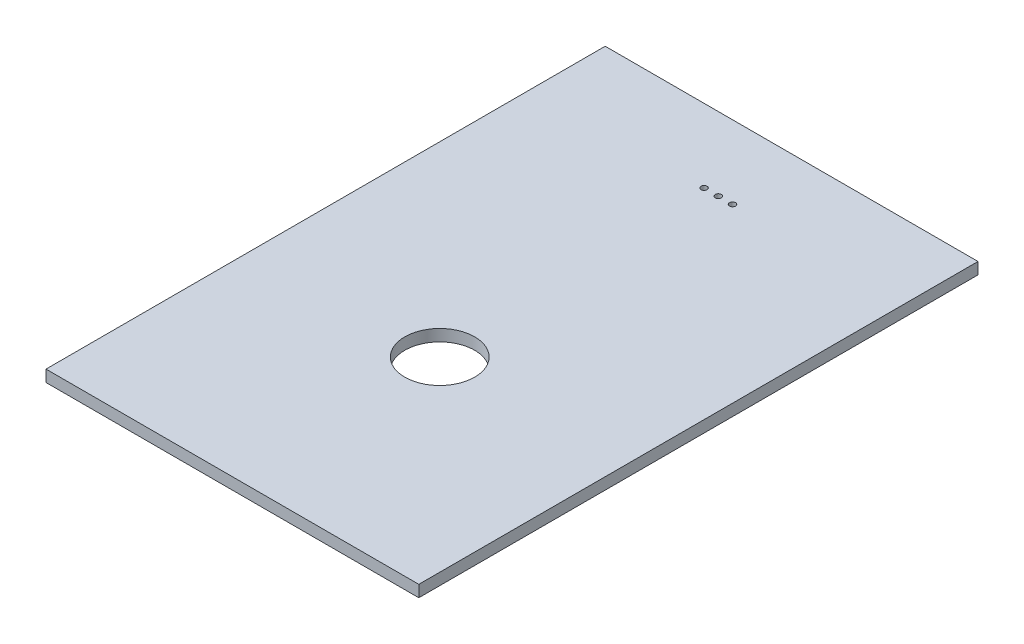
SolidWorks part; units mm, degrees
ref_plane "Front Plane" through (0, 0, 0) normal (0, 0, 1) x (1, 0, 0)
ref_plane "Top Plane" through (0, 0, 0) normal (0, 1, 0) x (1, 0, 0)
ref_plane "Right Plane" through (0, 0, 0) normal (1, 0, 0) x (0, 0, -1)
sketch "Sketch1" plane through (0, 0, 0) normal (0, 0, 1) x (1, 0, 0)
  line L7 (-101.6, -3.175) -> (101.6, -3.175)
  line L8 (-101.6, -3.175) -> (-101.6, 3.175)
  line L9 (-101.6, 3.175) -> (101.6, 3.175)
  line L10 (101.6, -3.175) -> (101.6, 3.175)
  line L11 (-101.6, -3.175) -> (101.6, 3.175) construction
  line L12 (-101.6, 3.175) -> (101.6, -3.175) construction
  point P4 (0, 0)
  point P14 (0, 0)
  dimension "Thickness" = 6.35
  dimension "Width" = 203.2
sketch "Sketch2" plane through (0, 0, 0) normal (0, 1, 0) x (0, 0, -1)
  line L0 (152.4, 101.6) -> (-152.4, 101.6) construction
  point P4 (0, 101.6)
  dimension "Length" = 304.8
sketch "Sketch3" plane through (0, 0, 0) normal (0, 0, 1) x (1, 0, 0)
  line L6 (-101.6, 3.175) -> (101.6, 3.175)
  line L7 (101.6, 3.175) -> (101.6, -3.175)
  line L8 (101.6, -3.175) -> (-101.6, -3.175)
  line L9 (-101.6, -3.175) -> (-101.6, 3.175)
extrude "Boss-Extrude1" add sketch "Sketch3" along normal mid plane 304.8
sketch "Sketch5" plane through (0, 3.175, 0) normal (0, 1, 0) x (1, 0, 0)
  circle A1 centre (7.7466, 112.45) radius 1.65
  circle A2 centre (-7.7454, 112.45) radius 1.65
  circle A3 centre (0.0006, 112.45) radius 1.65
  dimension "D1" = 3.3
  dimension "D2" = 3.3
  dimension "D3" = 3.3
extrude "Cut-Extrude1" cut sketch "Sketch5" against normal blind 25400
sketch "Sketch7" plane through (0, -3.175, 0) normal (0, 1, 0) x (1, 0, 0)
  circle A0 centre (7.7466, 112.45) radius 3.5255
  circle A1 centre (0.0006, 112.45) radius 3.5255
  circle A2 centre (-7.7454, 112.45) radius 3.5255
  dimension "D1" = 7.051
  dimension "D2" = 7.051
  dimension "D3" = 7.051
extrude "Cut-Extrude2" cut sketch "Sketch7" along normal blind 2.7991
sketch "Sketch8" plane through (0, 3.175, 0) normal (0, 1, 0) x (1, 0, 0)
  line L0 (101.6, 152.4) -> (0, 152.4) construction
  line L1 (101.6, 152.4) -> (-101.6, 152.4) construction
  line L2 (0, 152.4) -> (0, -39.3852) construction
  circle A0 centre (0, -39.3852) radius 19.05
  dimension "D1" = 191.7852
  dimension "D2" = 38.1
extrude "Cut-Extrude3" cut sketch "Sketch8" against normal through all
equation "\"D1@Boss-Extrude1\" = \"Length@Sketch2\""
